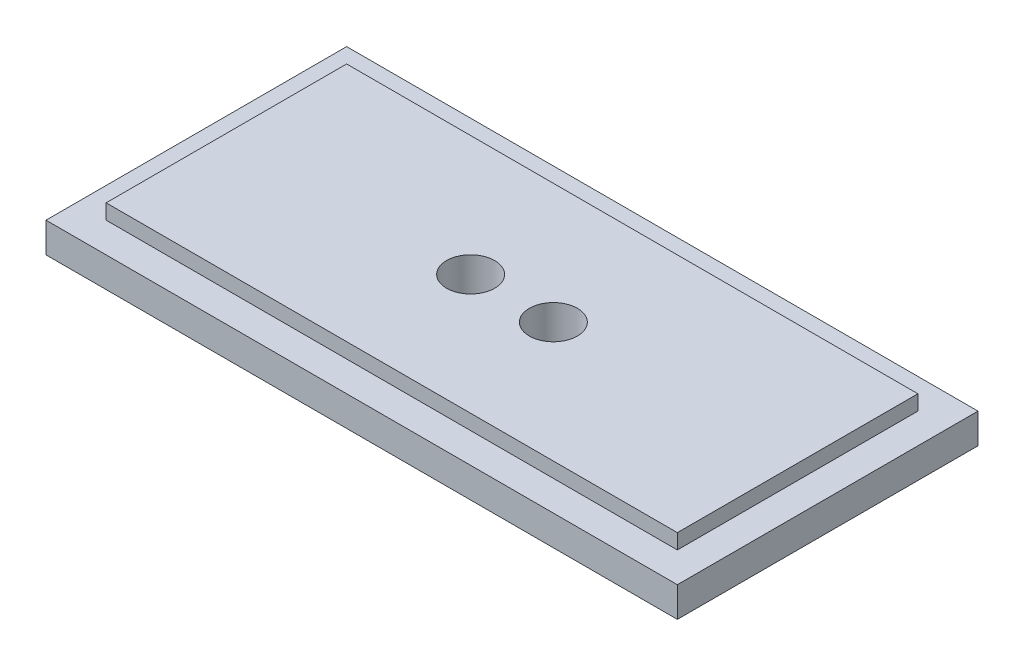
SolidWorks part; units mm, degrees
ref_plane "Front Plane" through (0, 0, 0) normal (0, 0, 1) x (1, 0, 0)
ref_plane "Top Plane" through (0, 0, 0) normal (0, 1, 0) x (1, 0, 0)
ref_plane "Right Plane" through (0, 0, 0) normal (1, 0, 0) x (0, 0, -1)
sketch "Sketch1" plane through (0, 0, 0) normal (0, 1, 0) x (1, 0, 0)
  line L1 (105, -50) -> (-105, -50)
  line L2 (105, -50) -> (105, 50)
  line L3 (105, 50) -> (-105, 50)
  line L4 (-105, -50) -> (-105, 50)
  line L5 (105, -50) -> (-105, 50) construction
  line L6 (105, 50) -> (-105, -50) construction
  point P0 (0, 0)
extrude "Boss-Extrude1" add sketch "Sketch1" along normal blind 10
sketch "Sketch2" plane through (0, 10, 0) normal (0, 1, 0) x (1, 0, 0)
  line L1 (95, -40) -> (-95, -40)
  line L2 (95, -40) -> (95, 40)
  line L3 (95, 40) -> (-95, 40)
  line L4 (-95, -40) -> (-95, 40)
  line L5 (95, -40) -> (-95, 40) construction
  line L6 (95, 40) -> (-95, -40) construction
  point P1 (0, 0)
extrude "Boss-Extrude2" add sketch "Sketch2" along normal blind 5
sketch "Sketch3" plane through (0, 0, 0) normal (0, -1, 0) x (1, 0, 0)
  line L0 (-28.5, -16) -> (-28.5, 16)
  line L1 (23.5, -11) -> (-23.5, -11)
  line L2 (23.5, -11) -> (23.5, 11)
  line L3 (23.5, 11) -> (-23.5, 11)
  line L4 (-23.5, -11) -> (-23.5, 11)
  line L5 (23.5, -11) -> (-23.5, 11) construction
  line L6 (23.5, 11) -> (-23.5, -11) construction
  line L7 (28.5, 16) -> (-28.5, 16)
  line L8 (28.5, -16) -> (28.5, 16)
  line L9 (28.5, -16) -> (-28.5, -16)
  point P0 (0, 0)
  dimension "D1" = 5
extrude "Boss-Extrude3" add sketch "Sketch3" along normal blind 15
sketch "Sketch4" plane through (0, 0, 0) normal (0, -1, 0) x (1, 0, 0)
  line L0 (-23.5, 0) -> (23.5, 0) construction
  line L1 (-23.5, 11) -> (-23.5, -11) construction
  line L2 (23.5, -11) -> (23.5, 11) construction
  line L3 (0, 0) -> (-13.76, 0) construction
  line L4 (0, 0) -> (0, 6.7622) construction
  circle A0 centre (-13.76, 0) radius 8
  circle A1 centre (13.76, 0) radius 8
extrude "Cut-Extrude1" cut sketch "Sketch4" against normal through all both and the other way through all
